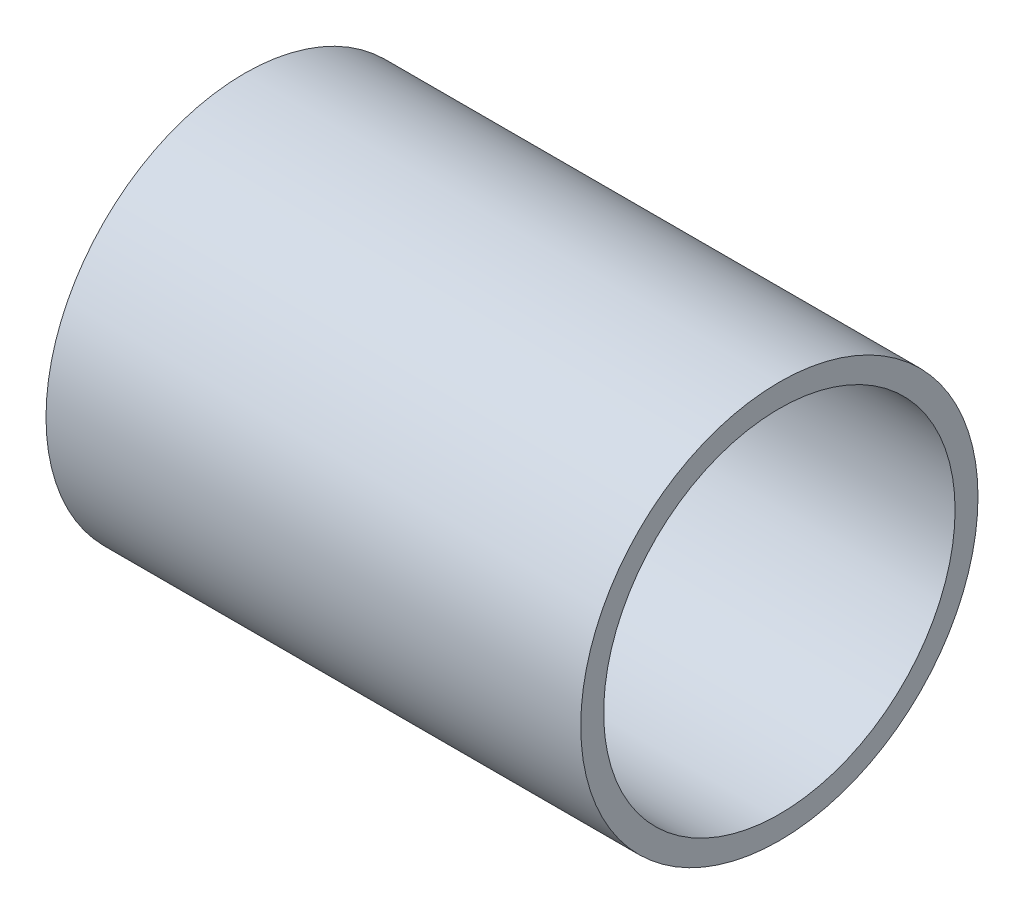
SolidWorks part; units mm, degrees
ref_plane "Front Plane" through (0, 0, 0) normal (0, 0, 1) x (1, 0, 0)
ref_plane "Top Plane" through (0, 0, 0) normal (0, 1, 0) x (1, 0, 0)
ref_plane "Right Plane" through (0, 0, 0) normal (1, 0, 0) x (0, 0, -1)
sketch "Sketch1" plane through (0, 0, 0) normal (1, 0, 0) x (0, 0, -1)
  circle A0 centre (0, 0) radius 23
  circle A1 centre (0, 0) radius 26
  dimension "D1" = 52
  dimension "D2" = 46
extrude "Boss-Extrude1" add sketch "Sketch1" against normal blind 70
